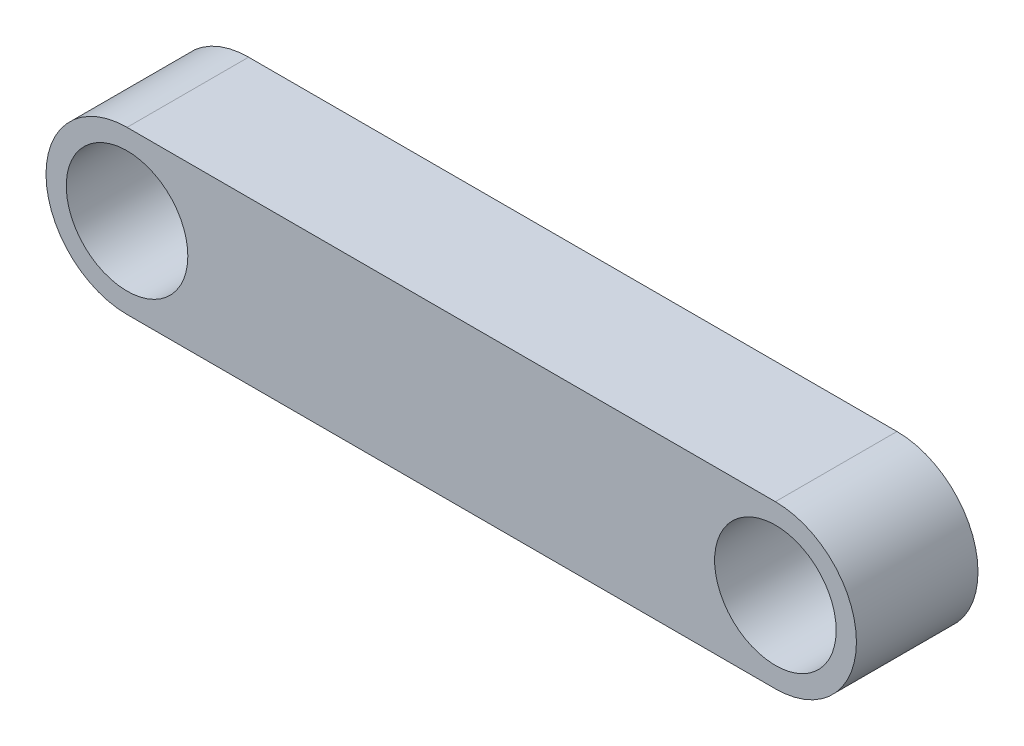
SolidWorks part; units mm, degrees
ref_plane "前视基准面" through (0, 0, 0) normal (0, 0, 1) x (1, 0, 0)
ref_plane "上视基准面" through (0, 0, 0) normal (0, 1, 0) x (1, 0, 0)
ref_plane "右视基准面" through (0, 0, 0) normal (1, 0, 0) x (0, 0, -1)
sketch "草图1" plane through (0, 0, 0) normal (0, 0, 1) x (1, 0, 0)
  line L0 (0, -322.5267) -> (0, 15803.8073) construction
  line L1 (-8, 2) -> (8, 2)
  line L2 (-8, -2) -> (8, -2)
  circle A0 centre (-8, 0) radius 2
  circle A1 centre (-8, 0) radius 1.5
  circle A2 centre (8, 0) radius 1.5
  circle A3 centre (8, 0) radius 2
  point P11 (0, -2)
  point P15 (0, 2)
  dimension "D1" = 4
  dimension "D2" = 8
  dimension "D3" = 3
extrude "凸台-拉伸1" add sketch "草图1" along normal blind 3 contours L2 L0 L1 A0 | A1 | L0 L2 A3 L1 | A3 A2
